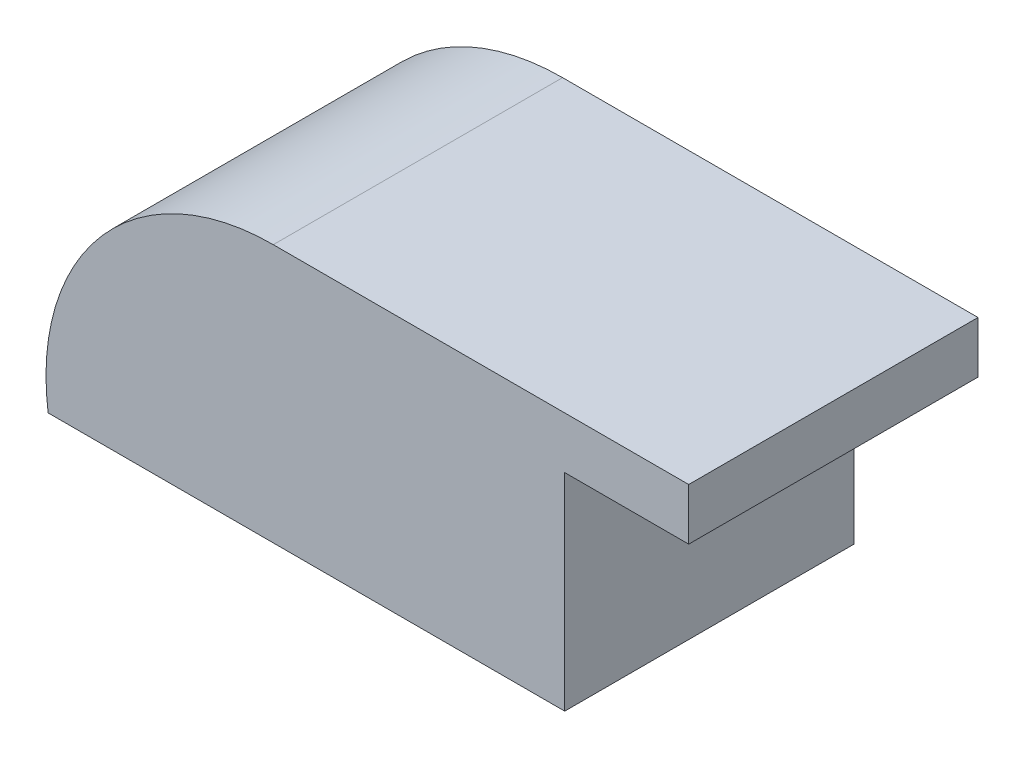
SolidWorks part; units mm, degrees
ref_plane "Front Plane" through (0, 0, 0) normal (0, 0, 1) x (1, 0, 0)
ref_plane "Top Plane" through (0, 0, 0) normal (0, 1, 0) x (1, 0, 0)
ref_plane "Right Plane" through (0, 0, 0) normal (1, 0, 0) x (0, 0, -1)
sketch "Sketch1" plane through (0, 0, 0) normal (0, 0, 1) x (1, 0, 0)
  line L0 (-8.8177, -6.0816) -> (16.1823, -6.0816)
  line L1 (16.1823, -6.0816) -> (16.1823, 3.9184)
  line L2 (16.1823, 3.9184) -> (22.1823, 3.9184)
  line L3 (22.1823, 3.9184) -> (22.1823, 6.4184)
  line L4 (22.1823, 6.4184) -> (2.0794, 6.4184)
  arc A1 (-8.8177, -6.0816) -> (2.0794, 6.4184) centre (2.0796, -4.5816) cw
  point P7 (0, 0)
  point P8 (2.0796, 6.4184)
  point P9 (0, 0)
  dimension "D1" = 25
  dimension "D2" = 10
  dimension "D3" = 2.5
  dimension "D4" = 6
extrude "Boss-Extrude1" add sketch "Sketch1" along normal blind 14
sketch "Sketch2" plane through (0, -6.0816, 0) normal (0, -1, 0) x (1, 0, 0)
  line L0 (-8.8177, 7) -> (16.1823, 7) construction
  line L1 (-8.8177, 14) -> (-8.8177, 0) construction
  line L2 (16.1823, 14) -> (16.1823, 0) construction
  circle A1 centre (7.9051, 7) radius 4
extrude "Cut-Extrude1" cut sketch "Sketch2" against normal blind 11
